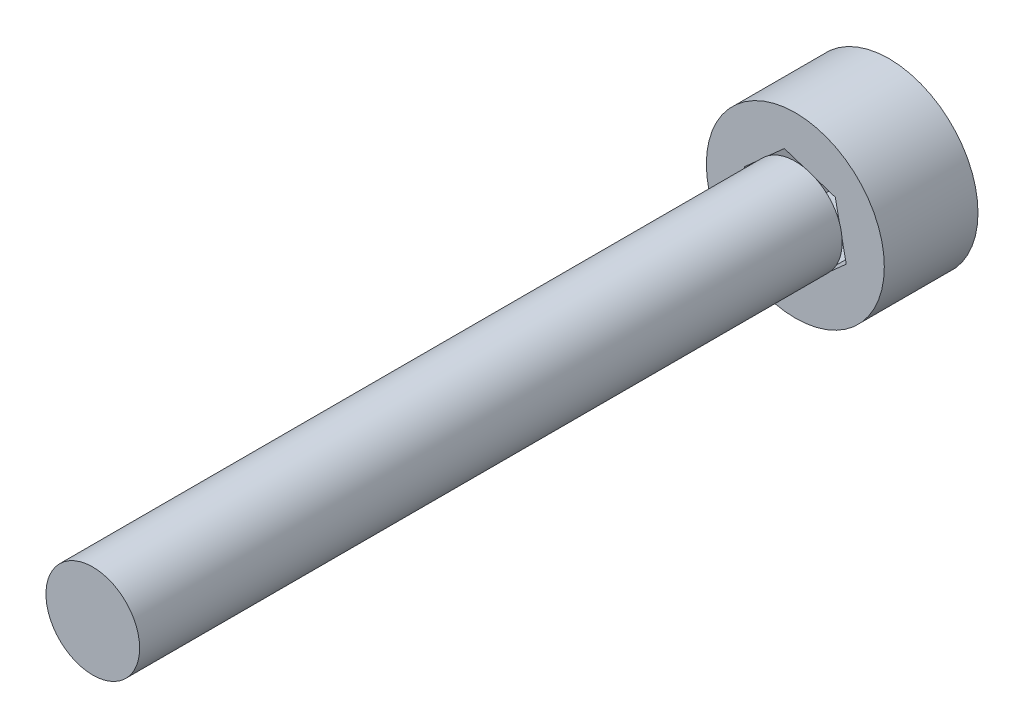
SolidWorks part; units mm, degrees
ref_plane "正面" through (0, 0, 0) normal (0, 0, 1) x (1, 0, 0)
ref_plane "平面" through (0, 0, 0) normal (0, 1, 0) x (1, 0, 0)
ref_plane "右側面" through (0, 0, 0) normal (1, 0, 0) x (0, 0, -1)
sketch "ｽｹｯﾁ1" plane through (0, 0, 0) normal (0, 0, 1) x (1, 0, 0)
  circle A0 centre (0, 0) radius 1.9
  dimension "D1" = 3.8
extrude "ﾎﾞｽ - 押し出し1" add sketch "ｽｹｯﾁ1" along normal blind 2
sketch "ｽｹｯﾁ2" plane through (0, 0, 2) normal (0, 0, 1) x (1, 0, 0)
  circle A0 centre (0, 0) radius 1
  dimension "D1" = 2
extrude "ﾎﾞｽ - 押し出し2" add sketch "ｽｹｯﾁ2" along normal blind 15
cosmetic thread "ねじ山1" parameters "D2"=1
sketch "ｽｹｯﾁ3" plane through (0, 0, 0) normal (0, 0, -1) x (-1, 0, 0)
  line L1 (0.8522, -0.7637) -> (1.0875, 0.3562)
  line L2 (1.0875, 0.3562) -> (0.2352, 1.1199)
  line L3 (0.2352, 1.1199) -> (-0.8522, 0.7637)
  line L4 (-0.8522, 0.7637) -> (-1.0875, -0.3562)
  line L5 (-1.0875, -0.3562) -> (-0.2352, -1.1199)
  line L6 (-0.2352, -1.1199) -> (0.8522, -0.7637)
  circle A0 centre (0, 0) radius 0.991 construction
extrude "ｶｯﾄ - 押し出し1" cut sketch "ｽｹｯﾁ3" against normal blind 2
